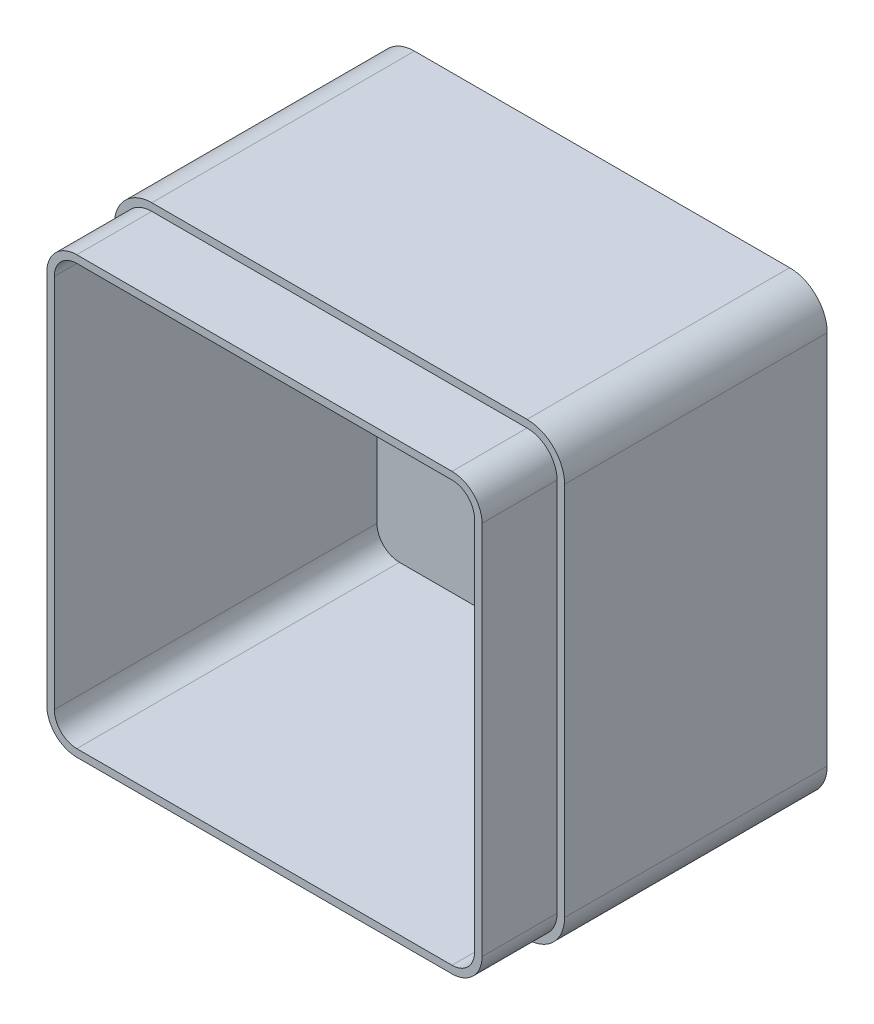
SolidWorks part; units mm, degrees
ref_plane "Front Plane" through (0, 0, 0) normal (0, 0, 1) x (1, 0, 0)
ref_plane "Top Plane" through (0, 0, 0) normal (0, 1, 0) x (1, 0, 0)
ref_plane "Right Plane" through (0, 0, 0) normal (1, 0, 0) x (0, 0, -1)
sketch "Sketch1" plane through (0, 0, 0) normal (0, 0, 1) x (1, 0, 0)
  line L1 (0, 0) -> (120, 0)
  line L2 (0, 0) -> (0, 120)
  line L3 (0, 120) -> (120, 120)
  line L4 (120, 0) -> (120, 120)
  dimension "D1" = 120
  dimension "D2" = 120
extrude "Boss-Extrude1" add sketch "Sketch1" along normal blind 90
fillet "Fillet1" radius 10 4 edges at (0, 0, 45) (120, 0, 45) (120, 120, 45) (0, 120, 45)
shell "Shell1" thickness 4
sketch "Sketch4" plane through (0, 0, 90) normal (0, 0, 1) x (1, 0, 0)
  line L0 (2, 110) -> (2, 10)
  line L1 (10, 2) -> (110, 2)
  line L2 (118, 10) -> (118, 110)
  line L3 (110, 118) -> (10, 118)
  line L4 (0, 110) -> (0, 10)
  line L5 (10, 0) -> (110, 0)
  line L6 (120, 10) -> (120, 110)
  line L7 (110, 120) -> (10, 120)
  line L8 (0, 110) -> (0, 10)
  line L9 (10, 0) -> (110, 0)
  line L10 (120, 10) -> (120, 110)
  line L11 (110, 120) -> (10, 120)
  arc A0 (2, 10) -> (10, 2) centre (10, 10) ccw
  arc A1 (110, 2) -> (118, 10) centre (110, 10) ccw
  arc A2 (118, 110) -> (110, 118) centre (110, 110) ccw
  arc A3 (10, 118) -> (2, 110) centre (10, 110) ccw
  arc A4 (0, 10) -> (10, 0) centre (10, 10) ccw
  arc A5 (110, 0) -> (120, 10) centre (110, 10) ccw
  arc A6 (120, 110) -> (110, 120) centre (110, 110) ccw
  arc A7 (10, 120) -> (0, 110) centre (10, 110) ccw
  arc A8 (0, 10) -> (10, 0) centre (10, 10) ccw
  arc A9 (110, 0) -> (120, 10) centre (110, 10) ccw
  arc A10 (120, 110) -> (110, 120) centre (110, 110) ccw
  arc A11 (10, 120) -> (0, 110) centre (10, 110) ccw
  dimension "D1" = 0
  dimension "D2" = 2
extrude "Cut-Extrude2" cut sketch "Sketch4" against normal blind 20
